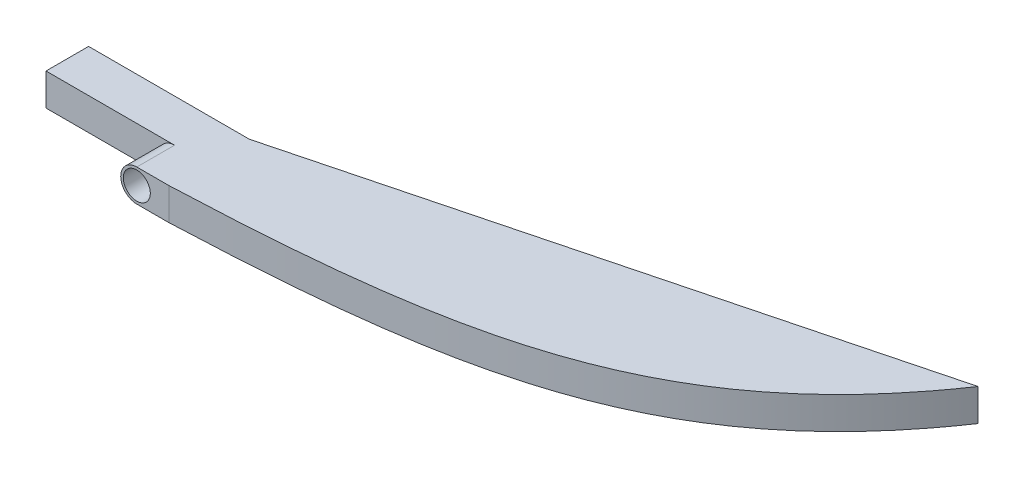
SolidWorks part; units mm, degrees
ref_plane "Alzado" through (0, 0, 0) normal (0, 0, 1) x (1, 0, 0)
ref_plane "Planta" through (0, 0, 0) normal (0, 1, 0) x (1, 0, 0)
ref_plane "Vista lateral" through (0, 0, 0) normal (1, 0, 0) x (0, 0, -1)
sketch "Croquis2" plane through (0, 0, 0) normal (0, 1, 0) x (1, 0, 0)
  line L0 (0, 0) -> (90, 0) construction
  line L1 (0, 0) -> (0, 12.5)
  line L2 (90, 0) -> (90, 39) construction
  line L3 (0, 12.5) -> (90, 35.8654)
  spline S0 degree 4 poles (-9.0097, -0.3032) (-8.7076, -0.2945) (-8.1243, -0.2777) (-7.1409, -0.2505) (-5.1439, -0.1858) (-3.7083, -0.1414) (-0.7618, -0.0308) (0.4754, 0.0183) (2.9924, 0.1252) (4.5799, 0.2009) (6.6126, 0.3012) (8.3923, 0.3988) (10.3159, 0.5099) (12.159, 0.6263) (14.5117, 0.7852) (17.3057, 0.9943) (20.1144, 1.2315) (22.9099, 1.4998) (25.7075, 1.7965) (29.4305, 2.2324) (34.4573, 2.9285) (39.9176, 3.8881) (45.327, 5.1051) (49.7699, 6.3191) (53.3462, 7.448) (56.8702, 8.731) (60.3296, 10.1801) (63.7103, 11.8049) (66.9976, 13.6115) (70.1773, 15.6016) (72.8543, 17.5009) (75.0672, 19.2371) (76.8547, 20.7526) (78.2502, 22.0046) (79.6197, 23.3032) (80.9624, 24.6475) (82.2773, 26.0361) (83.4032, 27.2889) (84.3454, 28.3827) (85.1155, 29.3069) (85.7227, 30.0536) (86.321, 30.8074) (86.9107, 31.5683) (87.4913, 32.335) (88.0643, 33.1098) (88.6299, 33.8921) (89.0999, 34.5557) (89.557, 35.2158) (89.908, 35.7289) (90.1259, 36.0512) (90.5206, 36.6414) (91.018, 37.3961) (91.5196, 38.1766) (92.1613, 39.1955) (92.8125, 40.2583) (93.4957, 41.4026) (94.1961, 42.6106) (94.7128, 43.5262) (95.0517, 44.1381) (95.2199, 44.4446) knots 0 0 0 0 0 0.009353 0.018706 0.037411 0.056117 0.074823 0.090398 0.105974 0.121549 0.137125 0.1527 0.168276 0.183851 0.199426 0.230577 0.261728 0.277304 0.292879 0.32403 0.386332 0.445925 0.477075 0.508226 0.539377 0.570528 0.601679 0.63283 0.66398 0.695131 0.726282 0.741858 0.757433 0.773009 0.788584 0.804577 0.82057 0.836563 0.844559 0.852555 0.860552 0.868548 0.876545 0.884541 0.892538 0.900535 0.908531 0.912529 0.916528 0.921147 0.925767 0.935007 0.944247 0.953487 0.965115 0.976743 0.988372 1 1 1 1 1 construction
  spline S1 degree 4 poles (0, 0) (0.3941, 0.0158) (1.195, 0.0488) (2.9924, 0.1252) (4.5799, 0.2009) (6.6126, 0.3012) (8.3923, 0.3988) (10.3159, 0.5099) (12.159, 0.6263) (14.5117, 0.7852) (17.3057, 0.9943) (20.1144, 1.2315) (22.9099, 1.4998) (25.7075, 1.7965) (29.4305, 2.2324) (34.4573, 2.9285) (39.9176, 3.8881) (45.327, 5.1051) (49.7699, 6.3191) (53.3462, 7.448) (56.8702, 8.731) (60.3296, 10.1801) (63.7103, 11.8049) (66.9976, 13.6115) (70.1773, 15.6016) (72.8543, 17.5009) (75.0672, 19.2371) (76.8547, 20.7526) (78.2502, 22.0046) (79.6197, 23.3032) (80.9624, 24.6475) (82.2773, 26.0361) (83.4032, 27.2889) (84.3454, 28.3827) (85.1155, 29.3069) (85.7227, 30.0536) (86.321, 30.8074) (86.9107, 31.5683) (87.4913, 32.335) (88.0643, 33.1098) (88.6299, 33.8921) (89.0999, 34.5557) (89.557, 35.2158) (89.8293, 35.6139) (89.9432, 35.7816) (90, 35.8654) knots 0.074823 0.074823 0.074823 0.074823 0.074823 0.090398 0.105974 0.121549 0.137125 0.1527 0.168276 0.183851 0.199426 0.230577 0.261728 0.277304 0.292879 0.32403 0.386332 0.445925 0.477075 0.508226 0.539377 0.570528 0.601679 0.63283 0.66398 0.695131 0.726282 0.741858 0.757433 0.773009 0.788584 0.804577 0.82057 0.836563 0.844559 0.852555 0.860552 0.868548 0.876545 0.884541 0.892538 0.900535 0.908531 0.912529 0.916528 0.916528 0.916528 0.916528 0.916528
  dimension "D4" = 35.8654
  dimension "D2" = 12.5
  dimension "D3" = 90
extrude "Saliente-Extruir1" add sketch "Croquis2" along normal blind 5
sketch "Croquis3" plane through (0, 0, 0) normal (-1, 0, 0) x (0, 0, 1)
  line L0 (0, 5) -> (0, 0) construction
  line L1 (-12.5, 0) -> (0, 0)
  line L2 (-12.5, 0) -> (-12.5, 5)
  line L3 (-12.5, 5) -> (0, 5)
  line L4 (0, 0) -> (0, 5)
  line L5 (-12.5, 0) -> (0, 5) construction
  line L6 (-12.5, 5) -> (0, 0) construction
  line L7 (-12.5, 2.5) -> (0, 2.5) construction
  line L8 (-12.5, 5) -> (-12.5, 0) construction
  point P0 (-6.25, 2.5)
  dimension "D1" = 12.5
  dimension "D2" = 5
extrude "Saliente-Extruir2" add sketch "Croquis3" along normal blind 25
sketch "Croquis4" plane through (0, 0, -12.5) normal (0, 0, -1) x (-1, 0, 0)
  line L0 (0, 2.5) -> (25, 2.5) construction
  line L1 (0, 5) -> (0, 0) construction
  line L2 (25, 5) -> (25, 0) construction
  line L14 (25, 5) -> (25, 0) construction
  circle A0 centre (5, 2.5) radius 2.1
  point P28 (25, 2.5)
  dimension "D1" = 4.2
  dimension "D2" = 20
extrude "Cortar-Extruir3" cut sketch "Croquis4" against normal blind 12.5 contours A0
sketch "Croquis5" plane through (0, 0, 0) normal (0, 0, 1) x (1, 0, 0)
  line L0 (-25, 5) -> (-16, 5)
  line L4 (-5, 0) -> (-25, 0)
  line L5 (-25, 0) -> (-25, 5)
  circle A0 centre (-5, 2.5) radius 2.5
  line M8 (0, 5) -> (-25, 5)
  line M9 (-25, 5) -> (-25, 0)
  line M10 (-25, 0) -> (0, 0)
  dimension "D2" = 5
extrude "Cortar-Extruir2" cut sketch "Croquis5" against normal blind 5.875 contours A0 M8 M9 M10
equation "\"D1@Croquis2\" = \"A_BASE\""
equation "\"D3@Croquis2\" = \"L_ALETA\""
equation "\"D2@Croquis2\" = \"A_BASE\""
equation "\"D1@Saliente-Extruir1\"=\"E_ALETA\""
equation "\"D1@Croquis3\"=\"A_BASE\""
equation "\"D2@Croquis3\"  = \"E_ALETA\""
equation "\"D1@Saliente-Extruir2\"=\"L_CAJA\""
equation "\"D1@Croquis4\"=\"R_SONDA\" * 2 +\"TOLERANCIA\""
equation "\"D2@Croquis4\"=\"D_SONDA\""
equation "\"A_BASE\"= \"L_DIE\" -  \"E_CAJA\""
equation "\"E_CE_SONDA\"= 0.1"
equation "\"L_DIE_SONDA\"= ( \"GAP_ALETAS\" / 4 )"
equation "\"D1@Croquis5\" = \"L_CONC\""
equation "\"D1@Cortar-Extruir2\" = \"A_BASE\" - ( ( \"A_CAJA\" - \"A_CONC\" ) / 2 )"
equation "\"OFFSET_SONDA_2\"= 1.000000"
equation "\"K\"= 1.5"
equation "\"L_CE\"= \"L_DIE\""
equation "\"D1@Croquis8\" = \"OFFSET_SONDA\""
equation "\"D1@Cortar-Extruir4\" = \"E_BASE\""
equation "\"D4@Croquis2\" = ( ( sqr ( 13 ) - 3 ) * \"W_ALETA\" ) / 8"
equation "\"A_ALETA\"= ( ( ( tan ( \"ANG_ALETA\" ) ) * \"L_ALETA\" ) + \"A_BASE\" - ( \"GAP_ALETAS\" / 2 ) )"
equation "\"A_CAJA\"= ( 2 * \"A_BASE\" ) + \"GAP_ALETAS\""
equation "\"L_ALETA\"=90.000000"
equation "\"TAU_ALETA\"= ( \"L_ALETA\" / ( log ( ( \"A_ALETA\" ) + 1 ) ) )"
equation "\"E_ALETA\"=5.000000"
equation "\"R_SONDA\"= 2.05"
equation "\"D_SONDA\"=20.000000"
equation "\"L_CAJA\"=25.000000"
equation "\"E_CAJA\"= 2.5"
equation "\"W_CAJA\"= \"A_CAJA\" * \"CONST_CAJA\""
equation "\"W_CONC\"= ( \"W_CAJA\" / \"CONST_CONC\" ) "
equation "\"A_CONC\"= ( \"A_CAJA\" / \"CONST_CONC\" )"
equation "\"L_CONC\"= \"D_SONDA\" - \"OFFSET_CONC\""
equation "\"W_ALETA\"=70.000000"
equation "\"GAP_ALETAS\"=1.500000"
equation "\"R_C_SONDA\"= 0.63"
equation "\"CONST_CONC\"=2.000000"
equation "\"L_DIE\"= 15"
equation "\"L_CI\"= 18"
equation "\"CONST_CAJA\"=2.000000"
equation "\"ANG_ALETA\"=15.000000"
equation "\"TOLERANCIA\"= 0.1"
equation "\"A_BASE\"= ( \"L_DIE\" - \"E_CAJA\" )"
equation "\"D1@Cortar-Extruir3\" = \"A_BASE\""
equation "\"OFFSET_CONC\"= ( 2 * \"R_TORNILLO\" )"
equation "\"R_TORNILLO\"=2.600000"
